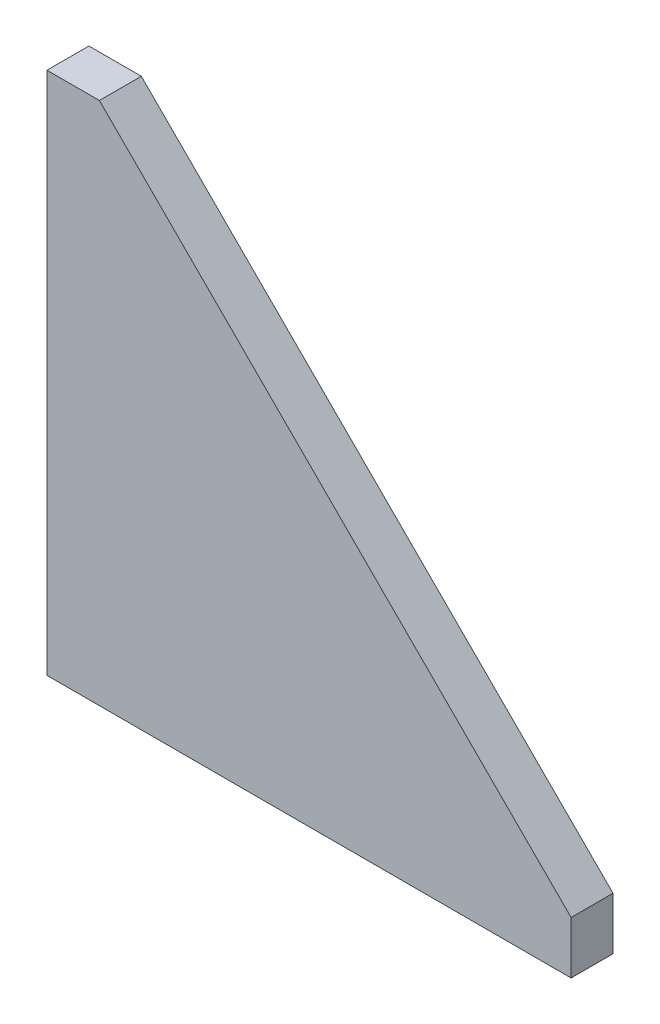
SolidWorks part; units mm, degrees
material "6061 合金"
ref_plane "前视基准面" through (0, 0, 0) normal (0, 0, 1) x (1, 0, 0)
ref_plane "上视基准面" through (0, 0, 0) normal (0, 1, 0) x (1, 0, 0)
ref_plane "右视基准面" through (0, 0, 0) normal (1, 0, 0) x (0, 0, -1)
other "Configuration Table"
sketch "Sketch1" plane through (0, 0, 0) normal (0, 0, 1) x (1, 0, 0)
  line L0 (0, 0) -> (150, 0)
  line L1 (150, 0) -> (150, 15)
  line L2 (150, 15) -> (15, 150)
  line L3 (15, 150) -> (0, 150)
  line L4 (0, 150) -> (0, 0)
extrude "Boss-Extrude1" add sketch "Sketch1" along normal blind 12
sketch "Sketch2" plane through (0, 0, 0) normal (0, 1, 0) x (1, 0, 0)
  circle A0 centre (33, -6) radius 2.5
  circle A1 centre (113, -6) radius 2.5
extrude "Cut-Extrude2" cut sketch "Sketch2" along normal blind 15
sketch "Sketch3" plane through (0, 0, 0) normal (1, 0, 0) x (0, 0, -1)
  circle A0 centre (-6, 50) radius 2.5
  circle A1 centre (-6, 120) radius 2.5
extrude "Cut-Extrude4" cut sketch "Sketch3" along normal blind 15
